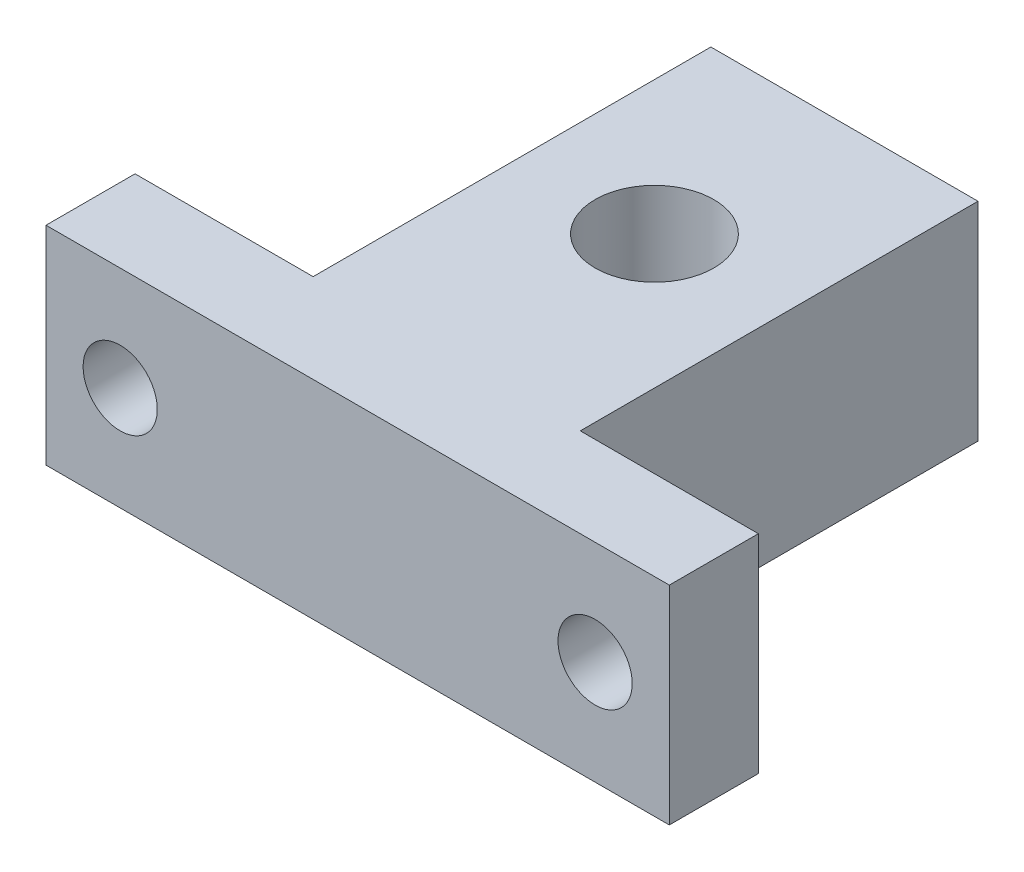
SolidWorks part; units mm, degrees
ref_plane "前视基准面" through (0, 0, 0) normal (0, 0, 1) x (1, 0, 0)
ref_plane "上视基准面" through (0, 0, 0) normal (0, 1, 0) x (1, 0, 0)
ref_plane "右视基准面" through (0, 0, 0) normal (1, 0, 0) x (0, 0, -1)
sketch "草图1" plane through (0, 0, 0) normal (0, 1, 0) x (1, 0, 0)
  line L0 (0, 18.3041) -> (0, -23.1789) construction
  line L1 (-21, -14) -> (21, -14)
  line L2 (-9, 12.8) -> (9, 12.8)
  line L3 (-9, 12.8) -> (-9, -20)
  line L4 (-9, -20) -> (9, -20)
  line L5 (9, 12.8) -> (9, -20)
  line L6 (-9, 12.8) -> (9, -20) construction
  line L7 (-9, -20) -> (9, 12.8) construction
  line L8 (-21, -14) -> (-21, -20)
  line L9 (-21, -20) -> (-9, -20)
  line L10 (21, -14) -> (21, -20)
  line L11 (21, -20) -> (9, -20)
  circle A0 centre (0, 0) radius 4
  point P5 (0, -3.6)
  point P12 (0, -14)
  dimension "D1" = 8
  dimension "D2" = 18
  dimension "D3" = 32.8
  dimension "D4" = 20
  dimension "D5" = 42
  dimension "D6" = 6
extrude "凸台-拉伸1" add sketch "草图1" along normal blind 14 contours L5 L2 L3 L1 A0 | L11 L10 L1 L5 | L5 L1 L3 L4 | L8 L9 L3 L1
sketch "草图2" plane through (0, 0, 14) normal (0, 0, -1) x (-1, 0, 0)
  line L0 (0, 19.6533) -> (0, -7.8555) construction
  line L1 (-21, 7) -> (27.2347, 7) construction
  line L2 (-21, 14) -> (-21, 0) construction
  circle A0 centre (-16, 7) radius 2.5
  circle A1 centre (16, 7) radius 2.5
  dimension "D1" = 5
  dimension "D2" = 32
extrude "切除-拉伸1" cut sketch "草图2" against normal blind 14
